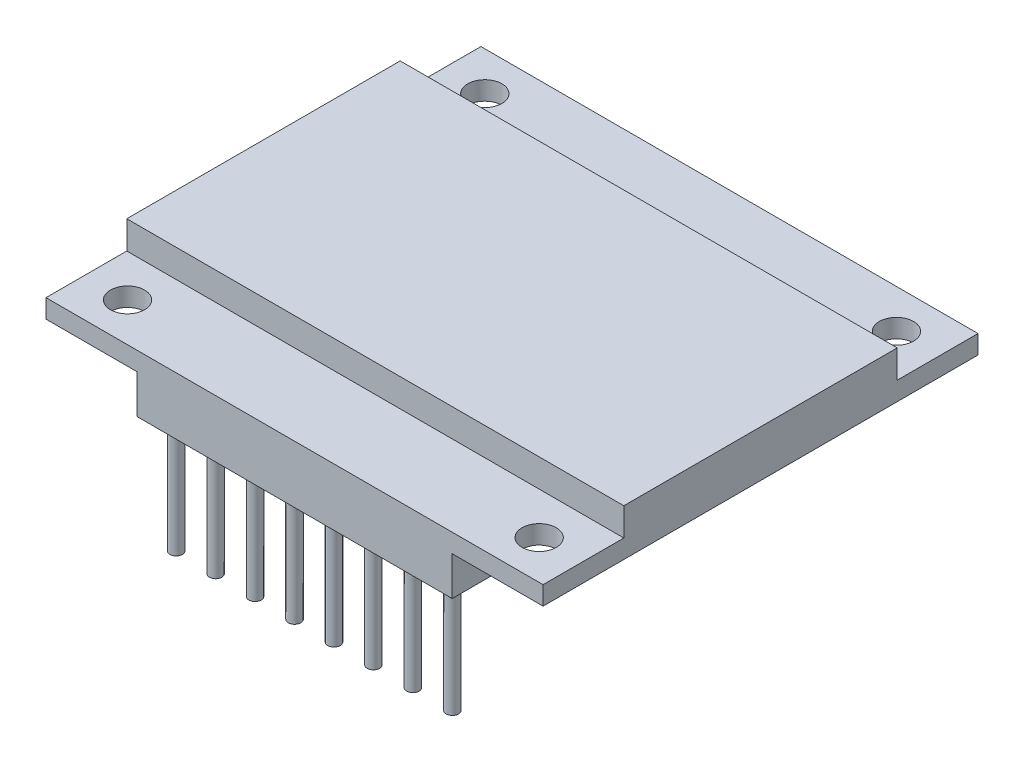
SolidWorks part; units mm, degrees
ref_plane "前视基准面" through (0, 0, 0) normal (0, 0, 1) x (1, 0, 0)
ref_plane "上视基准面" through (0, 0, 0) normal (0, 1, 0) x (1, 0, 0)
ref_plane "右视基准面" through (0, 0, 0) normal (1, 0, 0) x (0, 0, -1)
other "Configuration Table"
sketch "草图1" plane through (0, 0, 0) normal (0, 1, 0) x (1, 0, 0)
  line L1 (0, 0) -> (32, 0)
  line L2 (0, 0) -> (0, 28)
  line L3 (0, 28) -> (32, 28)
  line L4 (32, 0) -> (32, 28)
  dimension "D1" = 28
  dimension "D2" = 32
extrude "凸台-拉伸1" add sketch "草图1" along normal blind 1.2
sketch "草图2" plane through (0, 1.2, 0) normal (0, 1, 0) x (1, 0, 0)
  line L0 (0, 0) -> (32, 0) construction
  line L1 (0, 22.8) -> (32, 22.8)
  line L2 (0, 22.8) -> (0, 5.2)
  line L3 (0, 5.2) -> (32, 5.2)
  line L4 (32, 22.8) -> (32, 5.2)
  line L5 (0, 14) -> (38.8828, 14) construction
  line L6 (0, 28) -> (0, 0) construction
  dimension "D1" = 17.6
extrude "凸台-拉伸2" add sketch "草图2" along normal blind 1.8
sketch "草图3" plane through (0, 1.2, 0) normal (0, 1, 0) x (1, 0, 0)
  line L0 (0, 14) -> (36.6884, 14) construction
  line L1 (0, 22.8) -> (0, 5.2) construction
  line L2 (16, 28) -> (16, -4.3713) construction
  line L3 (32, 28) -> (0, 28) construction
  circle A0 centre (2.75, 25.5) radius 1.1
  circle A1 centre (2.75, 2.5) radius 1.1
  circle A2 centre (29.25, 2.5) radius 1.1
  circle A3 centre (29.25, 25.5) radius 1.1
  dimension "D1" = 2.2
  dimension "D2" = 23
  dimension "D3" = 26.5
extrude "切除-拉伸1" cut sketch "草图3" against normal through all
sketch "草图4" plane through (0, 0, 0) normal (0, -1, 0) x (1, 0, 0)
  line L0 (16, 0) -> (16, -28.8247) construction
  line L1 (0, 0) -> (32, 0) construction
  circle A0 centre (7.11, -1.27) radius 0.4
  circle A1 centre (9.65, -1.27) radius 0.4
  circle A2 centre (12.19, -1.27) radius 0.4
  circle A3 centre (14.73, -1.27) radius 0.4
  circle A4 centre (17.27, -1.27) radius 0.4
  circle A5 centre (19.81, -1.27) radius 0.4
  circle A6 centre (22.35, -1.27) radius 0.4
  circle A7 centre (24.89, -1.27) radius 0.4
  point P7 (8.6603, -1.27)
  dimension "D1" = 0.8
  dimension "D2" = 1.27
  dimension "D4" = 8.89
  dimension "D5" = 2.54
  dimension "D3" = 8
extrude "凸台-拉伸3" add sketch "草图4" along normal blind 10
sketch "草图5" plane through (0, 0, 0) normal (0, -1, 0) x (1, 0, 0)
  line L0 (0, 0) -> (32, 0) construction
  line L1 (5.85, 0) -> (26.15, 0)
  line L2 (5.85, 0) -> (5.85, -2.5)
  line L3 (5.85, -2.5) -> (26.15, -2.5)
  line L4 (26.15, 0) -> (26.15, -2.5)
  line L5 (16, -28) -> (16, -8.4621) construction
  line L6 (32, -28) -> (0, -28) construction
  dimension "D1" = 2.5
  dimension "D2" = 10.15
  dimension "D3" = 20.3
extrude "凸台-拉伸4" add sketch "草图5" along normal blind 2.5
